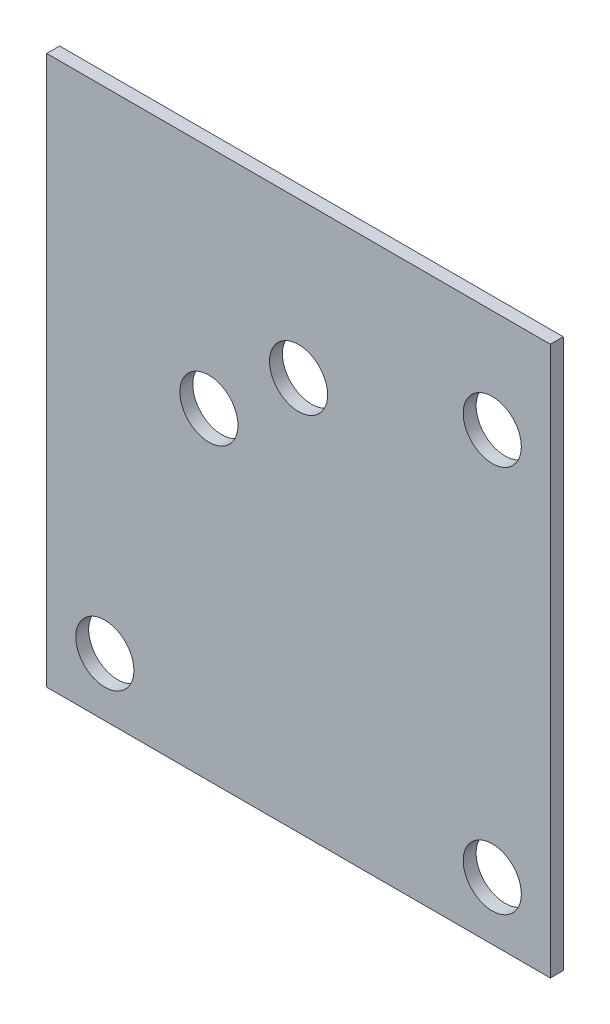
SolidWorks part; units mm, degrees
material "ABS PC"
ref_plane "Front Plane" through (0, 0, 0) normal (0, 0, 1) x (1, 0, 0)
ref_plane "Top Plane" through (0, 0, 0) normal (0, 1, 0) x (1, 0, 0)
ref_plane "Right Plane" through (0, 0, 0) normal (1, 0, 0) x (0, 0, -1)
sketch "Sketch1" plane through (0, 0, 0) normal (0, 0, 1) x (1, 0, 0)
  line L0 (-190.5, 0) -> (0, 0) construction
  line L1 (0, 0) -> (-139.3229, 129.9207) construction
  line L2 (-95.25, 164.9778) -> (0, 0) construction
  line L3 (0, 0) -> (0, 190.5) construction
  line L4 (28.575, -28.575) -> (28.575, 241.3)
  line L5 (28.575, -28.575) -> (-219.075, -28.575)
  line L6 (28.575, 241.3) -> (-219.075, 241.3)
  line L7 (-219.075, -28.575) -> (-219.075, 241.3)
  circle A0 centre (0, 0) radius 14.2875
  circle A1 centre (-190.5, 0) radius 14.2875
  circle A2 centre (-139.3229, 129.9207) radius 14.2875
  circle A3 centre (-95.25, 164.9778) radius 14.2875
  circle A4 centre (0, 190.5) radius 14.2875
  point P11 (-134.7038, 134.7038)
  dimension "D1" = 28.575
  dimension "D2" = 28.575
  dimension "D3" = 28.575
  dimension "D4" = 28.575
  dimension "D5" = 28.575
  dimension "D6" = 190.5
  dimension "D7" = 190.5
  dimension "D8" = 190.5
  dimension "D9" = 190.5
  dimension "D10" = 43
  dimension "D11" = 17
  dimension "D12" = 30
  dimension "D13" = 28.575
  dimension "D14" = 28.575
  dimension "D15" = 50.8
  dimension "D16" = 28.575
extrude "I CAN CHANGE THESE NAMES?!" add sketch "Sketch1" along normal blind 6.35
